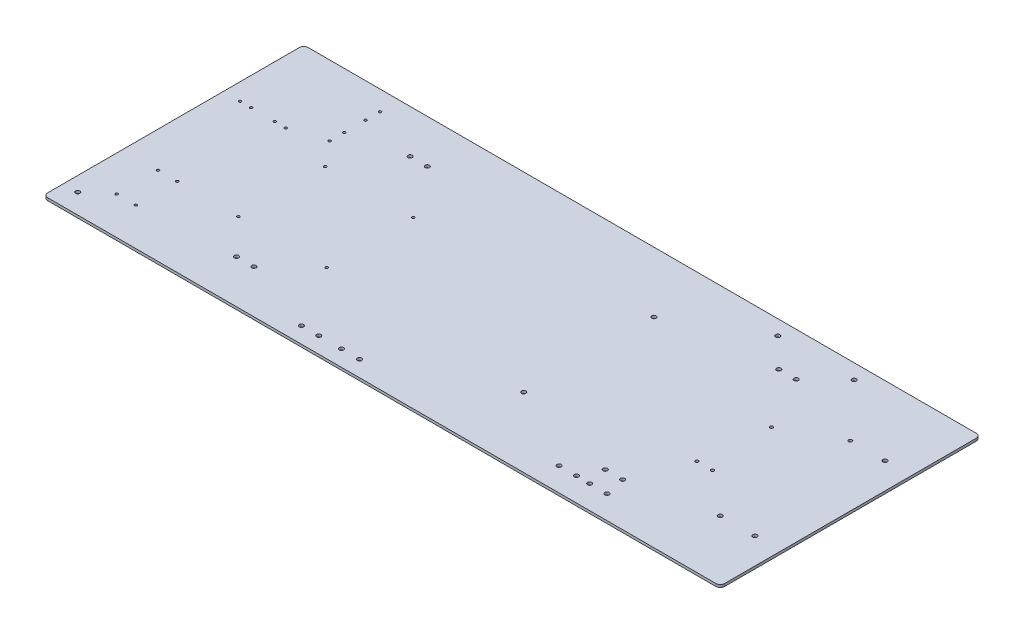
SolidWorks part; units mm, degrees
ref_plane "Front Plane" through (0, 0, 0) normal (0, 0, 1) x (1, 0, 0)
ref_plane "Top Plane" through (0, 0, 0) normal (0, 1, 0) x (1, 0, 0)
ref_plane "Right Plane" through (0, 0, 0) normal (1, 0, 0) x (0, 0, -1)
sketch "Sketch2" plane through (0, 0, 0) normal (0, 1, 0) x (1, 0, 0)
  line L1 (-390, 150) -> (390, 150)
  line L2 (-390, 150) -> (-390, -150)
  line L3 (-390, -150) -> (390, -150)
  line L4 (390, 150) -> (390, -150)
  dimension "D1" = 780
  dimension "D2" = 300
  dimension "D3" = 390
  dimension "D4" = 150
extrude "Boss-Extrude1" add sketch "Sketch2" along normal blind 3
fillet "Fillet1" radius 5 4 edges at (390, 1.5, -150) (390, 1.5, 150) (-390, 1.5, 150) (-390, 1.5, -150)
sketch "Sketch4" plane through (0, 3, 0) normal (0, 1, 0) x (1, 0, 0)
  line L0 (-385, -150) -> (385, -150) construction
  line L1 (390, -145) -> (390, 145) construction
  line L2 (385, 150) -> (-385, 150) construction
  line L3 (-390, 145) -> (-390, -145) construction
  circle A14 centre (83.3215, 80.2954) radius 2.5
  circle A15 centre (83.3215, -69.8031) radius 2.5
  circle A18 centre (173.53, 132.8053) radius 2.5
  circle A19 centre (261.45, 132.8053) radius 2.5
  circle A20 centre (207.49, 100) radius 2.5
  circle A21 centre (227.49, 100) radius 2.5
  circle A22 centre (-217.48, 100) radius 2.5
  circle A23 centre (-197.48, 100) radius 2.5
  circle A29 centre (-256.3506, 40.9525) radius 1.5
  circle A30 centre (-154.6576, 40.9525) radius 1.5
  circle A31 centre (-154.6576, -58.9972) radius 1.5
  circle A32 centre (-256.3506, -58.9972) radius 1.5
  circle A44 centre (360, -80) radius 2.5
  circle A49 centre (270, -38.9289) radius 1.75
  circle A52 centre (261, 38.0711) radius 1.75
  circle A53 centre (-279.343, 127.3305) radius 1.5
  circle A54 centre (-279.343, 110.4786) radius 1.5
  circle A55 centre (-279.343, 86.0722) radius 1.5
  circle A56 centre (-279.343, 69.2203) radius 1.5
  circle A57 centre (-330.2929, 56.8488) radius 1.5
  circle A58 centre (-317.5086, 56.8488) radius 1.5
  circle A59 centre (-370.5066, 57.1449) radius 1.5
  circle A60 centre (-357.7223, 57.1449) radius 1.5
  circle A61 centre (-348.9078, -58.986) radius 1.5
  circle A62 centre (-326.8259, -58.986) radius 1.5
  circle A63 centre (-348.9078, -106.6365) radius 1.5
  circle A64 centre (-326.8259, -106.6365) radius 1.5
  circle A65 centre (-373.3681, -127.1256) radius 2.5
  circle A66 centre (-111.2169, -131.5368) radius 2.5
  circle A67 centre (-91.1462, -131.5368) radius 2.5
  circle A68 centre (-65.0265, -131.5368) radius 2.5
  circle A69 centre (-44.1449, -131.5368) radius 2.5
  circle A70 centre (360, 70) radius 2.5
  circle A72 centre (177.0351, -122.8182) radius 2.5
  circle A73 centre (197.1058, -122.8182) radius 2.5
  circle A74 centre (207.49, -100) radius 2.5
  circle A75 centre (227.49, -100) radius 2.5
  circle A80 centre (320, -80) radius 2.5
  circle A81 centre (320, 70) radius 2
  circle A82 centre (252, -38.9289) radius 1.75
  circle A83 centre (212.4855, -123.057) radius 2.5
  circle A84 centre (232.5562, -123.057) radius 2.5
  circle A85 centre (-217.48, -100) radius 2.5
  circle A86 centre (-197.48, -100) radius 2.5
  point P2 (0, 0)
  point P3 (0, 0)
  point P4 (0, 0)
  point P21 (0, 0)
  point P22 (0, 0)
  point P23 (0, 0)
  point P28 (0, 0)
  point P29 (0, 0)
  point P32 (0, 0)
  point P33 (0, 0)
  point P34 (0, 0)
  point P35 (0, 0)
  point P36 (261, -62.5332)
  point P39 (261, 94.5698)
  point P40 (0, 0)
  point P41 (0, 0)
  point P42 (0, 0)
  point P47 (0, 0)
  point P48 (0, 0)
  point P49 (0, 0)
  point P50 (0, 0)
  point P51 (0, 0)
  point P54 (266.44, 102.8287)
  point P55 (0, 0)
  point P56 (0, 0)
  point P57 (0, 0)
  point P62 (266.44, 132.3183)
  point P63 (0, 0)
  point P72 (0, 0)
  point P77 (0, 0)
  point P78 (0, 0)
  point P79 (0, 0)
  point P92 (0, 0)
  point P93 (0, 0)
  point P106 (0, 0)
  point P107 (0, 0)
  point P108 (0, 0)
  dimension "D1" = 150
  dimension "D6" = 77
  dimension "D8" = 50
  dimension "D9" = 9
  dimension "D12" = 87.92
  dimension "D2" = 30
  dimension "D3" = 150
  dimension "D4" = 40
  dimension "D5" = 80
  dimension "D7" = 162.51
  dimension "D10" = 18
  dimension "D11" = 20
  dimension "D13" = 33.96
  dimension "D14" = 50
  dimension "D15" = 50
  dimension "D16" = 172.52
  dimension "D17" = 20
  dimension "D18" = 50
  dimension "D19" = 20
  dimension "D20" = 50
extrude "Cut-Extrude3" cut sketch "Sketch4" against normal blind 10
